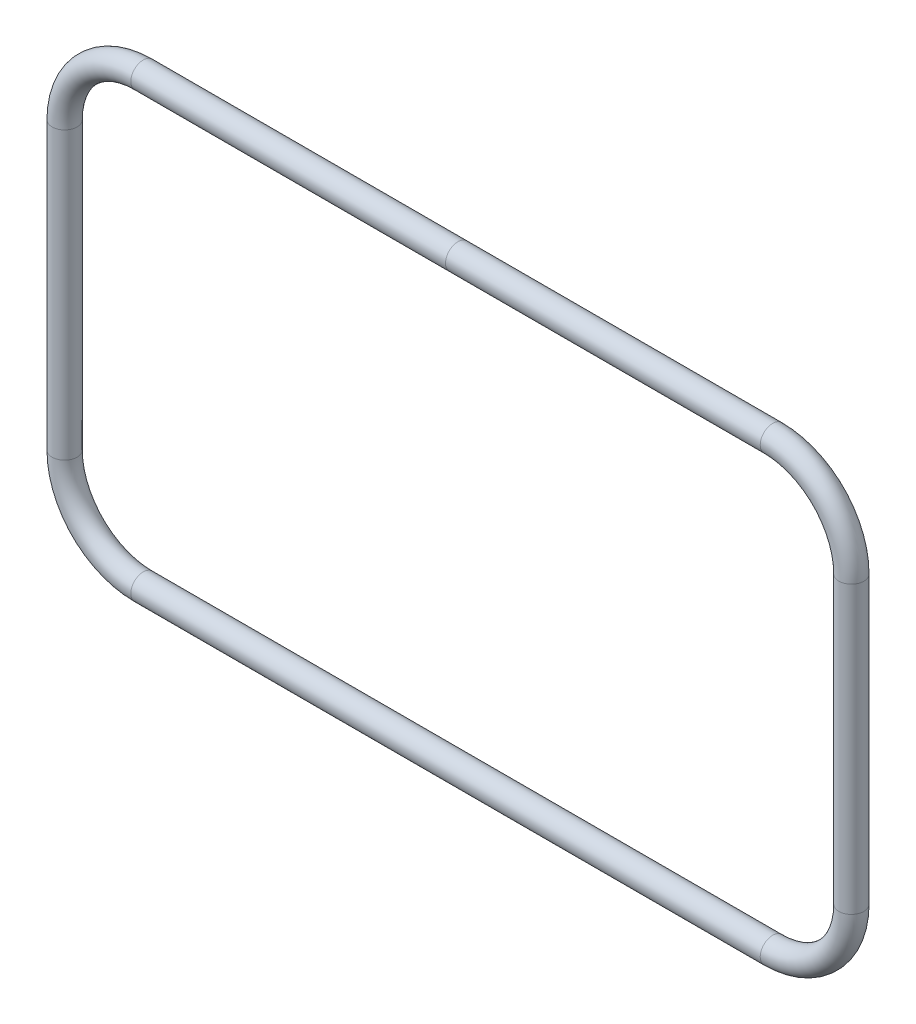
SolidWorks part; units mm, degrees
material "1.0035 (S185)"
ref_plane "Plano frontal" through (0, 0, 0) normal (0, 0, 1) x (1, 0, 0)
ref_plane "Plano superior" through (0, 0, 0) normal (0, 1, 0) x (1, 0, 0)
ref_plane "Plano direito" through (0, 0, 0) normal (1, 0, 0) x (0, 0, -1)
sketch "Esboço1" plane through (0, 0, 0) normal (0, 0, 1) x (1, 0, 0)
  line L1 (-150, 84.525) -> (150, 84.525) construction
  line L2 (-150, 84.525) -> (-150, -84.525) construction
  line L3 (-150, -84.525) -> (150, -84.525) construction
  line L4 (150, 84.525) -> (150, -84.525) construction
  line L5 (-150, 84.525) -> (150, -84.525) construction
  line L6 (-150, -84.525) -> (150, 84.525) construction
  line L7 (120, -84.525) -> (-120, -84.525)
  line L8 (150, -54.525) -> (150, 54.525)
  line L9 (120, 84.525) -> (-120, 84.525)
  line L10 (-150, -54.525) -> (-150, 54.525)
  line L11 (150, -84.525) -> (-150, 84.525) construction
  line L12 (150, 84.525) -> (-150, -84.525) construction
  arc A0 (-150, -54.525) -> (-120, -84.525) centre (-120, -54.525) ccw
  arc A1 (120, -84.525) -> (150, -54.525) centre (120, -54.525) ccw
  arc A2 (150, 54.525) -> (120, 84.525) centre (120, 54.525) ccw
  arc A3 (-120, 84.525) -> (-150, 54.525) centre (-120, 54.525) ccw
  point P0 (0, 0)
  point P6 (0, 0)
  dimension "D3" = 30
  dimension "D1" = 300
  dimension "D2" = 169.05
sketch "Esboço2" plane through (0, 0, 0) normal (1, 0, 0) x (0, 0, -1)
  circle A0 centre (0, 84.525) radius 4.7625
  dimension "D1" = 9.525
sweep "Varredura1" add profiles "Esboço2" path "Esboço1"
ref_plane "Plano1" through (0, 0, 10) normal (0, 0, 1) x (1, 0, 0)
ref_plane "Plano2" through (-120, 0, 0) normal (1, 0, 0) x (0, 0, -1)
ref_plane "Plano3" through (120, 0, 0) normal (1, 0, 0) x (0, 0, -1)
